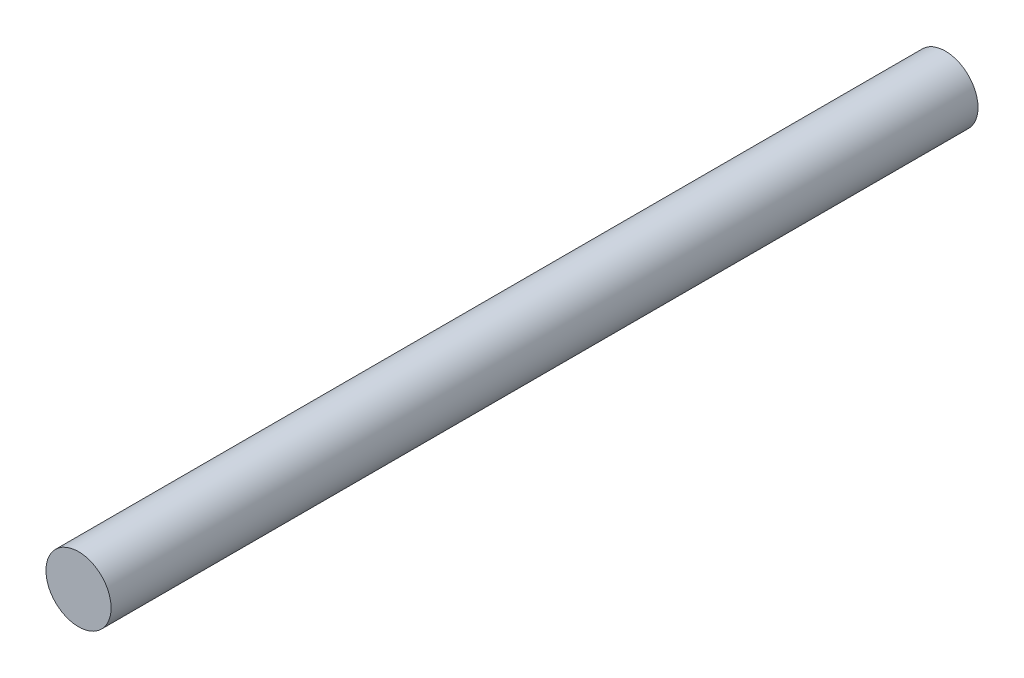
SolidWorks part; units mm, degrees
ref_plane "Front Plane" through (0, 0, 0) normal (0, 0, 1) x (1, 0, 0)
ref_plane "Top Plane" through (0, 0, 0) normal (0, 1, 0) x (1, 0, 0)
ref_plane "Right Plane" through (0, 0, 0) normal (1, 0, 0) x (0, 0, -1)
sketch "Sketch1" plane through (0, 0, 0) normal (0, 0, 1) x (1, 0, 0)
  circle A1 centre (0.0523, 0.183) radius 3.25
  dimension "D2" = 6.5
extrude "Boss-Extrude1" add sketch "Sketch1" along normal blind 86.5
